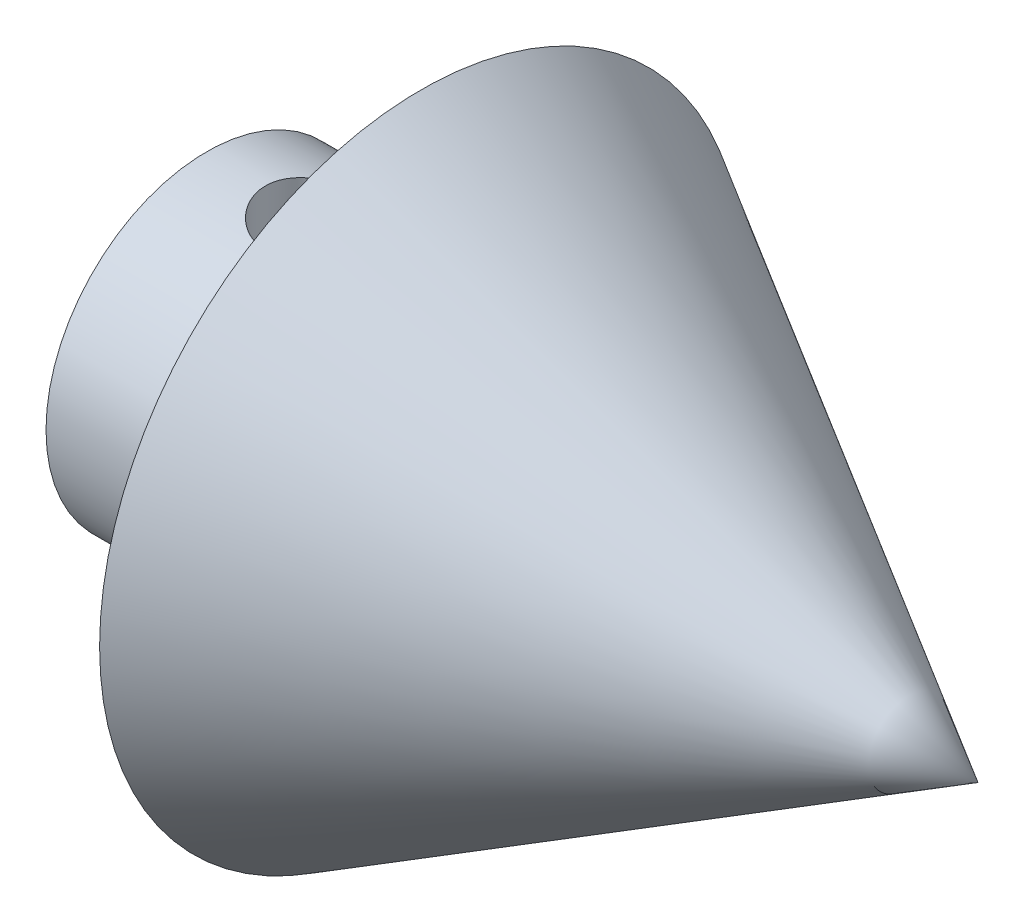
SolidWorks part; units mm, degrees
ref_plane "Alzado" through (0, 0, 0) normal (0, 0, 1) x (1, 0, 0)
ref_plane "Planta" through (0, 0, 0) normal (0, 1, 0) x (1, 0, 0)
ref_plane "Vista lateral" through (0, 0, 0) normal (1, 0, 0) x (0, 0, -1)
sketch "Croquis1" plane through (0, 0, 0) normal (1, 0, 0) x (0, 0, -1)
  line L0 (0, 7.5) -> (0, -7.5) construction
  line L1 (-7.5, 0) -> (7.5, 0) construction
  circle A0 centre (0, 0) radius 7.5
  dimension "D1" = 15
extrude "Saliente-Extruir1" add sketch "Croquis1" along normal blind 10
sketch "Croquis2" plane through (10, 0, 0) normal (1, 0, 0) x (0, 0, -1)
  line L0 (0, 15) -> (0, -15) construction
  circle A0 centre (0, 0) radius 15
  dimension "D1" = 30
extrude "Saliente-Extruir2" add sketch "Croquis2" along normal blind 30 draft 30 separate body
sketch "Croquis5" plane through (0, 0, 0) normal (-1, 0, 0) x (0, 0, 1)
  circle A0 centre (0, 0) radius 4.05
  dimension "D1" = 8.1
extrude "Cortar-Extruir1" cut sketch "Croquis5" against normal blind 15
sketch "Croquis8" plane through (0, 0, 0) normal (-1, 0, 0) x (0, 0, 1)
  line L0 (0, 0) -> (0, 7.5) construction
  circle A0 centre (0, 0) radius 7.5 construction
hole_wizard "Taladro de margen para #81" positions "Croquis3D3" profile "Croquis9" hole size "#8" standard "Ansi Inch" end condition up to next
sketch3d "Croquis3D3"
  line L0 (0, 0, 0) -> (10, 0, 0) construction
  line L1 (10, 0, 0) -> (35.9808, 0, 0) construction
  line L2 (10, 0, 0) -> (0, 0, 0) construction
  point P0 (5, 7.5, 0.0155)
  dimension "D1" = 5
sketch "Croquis9" plane through (5, 7.5, 0.0155) normal (1, 0, 0) x (0, -0.0021, 1)
  line L0 (0, 0) -> (0, 7.5)
  line L1 (0, 7.5) -> (2.2479, 7.5)
  line L2 (2.2479, 7.5) -> (2.2479, 0)
  line L5 (2.2479, 0) -> (0, 0)
  line L11 (0, -6.35) -> (0, 107.95) construction
  dimension "Diámetro de taladro hasta el siguiente" = 4.4958
  dimension "Profundidad de taladro hasta el siguiente" = 7.5
